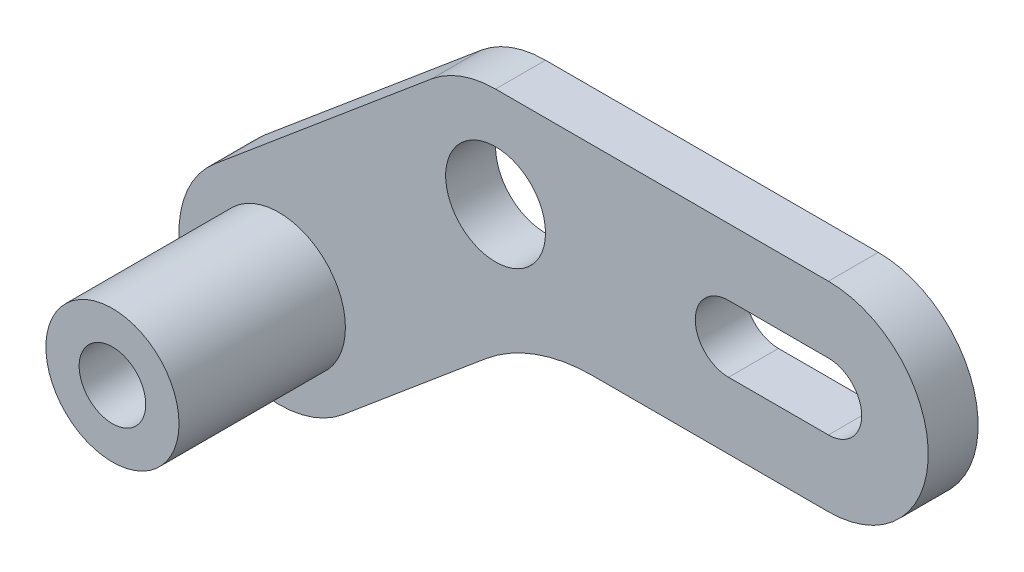
SolidWorks part; units mm, degrees
ref_plane "Спереди" through (0, 0, 0) normal (0, 0, 1) x (1, 0, 0)
ref_plane "Сверху" through (0, 0, 0) normal (0, 1, 0) x (1, 0, 0)
ref_plane "Справа" through (0, 0, 0) normal (1, 0, 0) x (0, 0, -1)
sketch "Эскиз1" plane through (0, 0, 0) normal (0, 0, 1) x (1, 0, 0)
  line L0 (0, 0) -> (-20, 0) construction
  line L1 (-20, 0) -> (-33.0228, -10.9274) construction
  line L2 (0, 6) -> (-20, 6)
  line L3 (0, -6) -> (-20, -6)
  line L4 (-36.8795, -6.3311) -> (-23.8567, 4.5963)
  line L5 (-29.166, -15.5237) -> (-16.1433, -4.5963)
  line L6 (-6, 0) -> (0, 0) construction
  line L7 (-6, 2) -> (0, 2)
  line L8 (-6, -2) -> (0, -2)
  circle A0 centre (0, 0) radius 6
  circle A1 centre (-33.0228, -10.9274) radius 6
  circle A2 centre (-20, 0) radius 6
  arc A3 (-6, 2) -> (-6, -2) centre (-6, 0) ccw
  circle A4 centre (-20, 0) radius 3
  circle A5 centre (-33.0228, -10.9274) radius 2
  arc A6 (0, -2) -> (0, 2) centre (0, 0) ccw
  point P18 (-3, 0)
  dimension "D1" = 12
  dimension "D5" = 12
  dimension "D6" = 2
  dimension "D7" = 6
  dimension "D8" = 4
  dimension "D2" = 140
  dimension "D3" = 20
  dimension "D4" = 17
  dimension "D9" = 6
extrude "Бобышка-Вытянуть1" add sketch "Эскиз1" along normal blind 3
fillet "Скругление1" radius 10 1 edges at (-17.8162, -6, 1.5)
sketch "Эскиз2" plane through (0, 0, 3) normal (0, 0, 1) x (1, 0, 0)
  circle A0 centre (-33.0228, -10.9274) radius 4
  circle A1 centre (-33.0228, -10.9274) radius 2
  circle A2 centre (-33.0228, -10.9274) radius 2 construction
  dimension "D1" = 8
extrude "Бобышка-Вытянуть2" add sketch "Эскиз2" along normal blind 10
